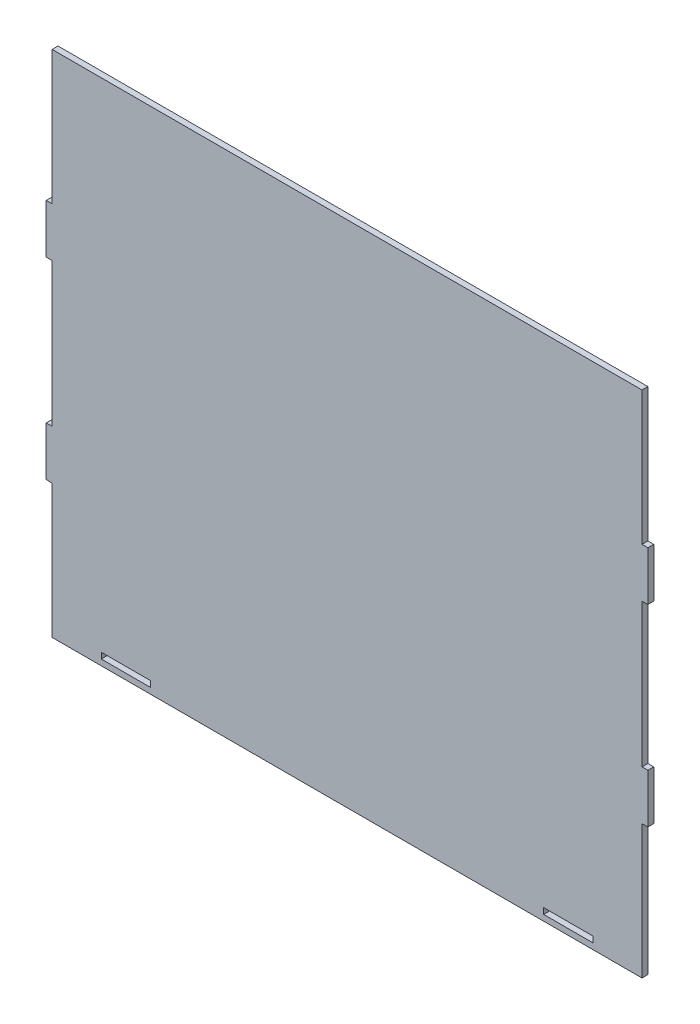
SolidWorks part; units mm, degrees
material "Maple"
ref_plane "Front Plane" through (0, 0, 0) normal (0, 0, 1) x (1, 0, 0)
ref_plane "Top Plane" through (0, 0, 0) normal (0, 1, 0) x (1, 0, 0)
ref_plane "Right Plane" through (0, 0, 0) normal (1, 0, 0) x (0, 0, -1)
sketch "Sketch1" plane through (0, 0, 0) normal (0, 0, 1) x (1, 0, 0)
  line L0 (-450, 0) -> (0, 0) construction
  line L1 (-300, 259) -> (300, 259)
  line L2 (-300, 259) -> (-300, 123)
  line L3 (-300, -259) -> (300, -259)
  line L4 (300, 259) -> (300, 123)
  line L5 (-300, 259) -> (300, -259) construction
  line L6 (-300, -259) -> (300, 259) construction
  line L7 (-306, 123) -> (-300, 123)
  line L8 (-306, 123) -> (-306, 73)
  line L9 (-306, 73) -> (-300, 73)
  line L11 (-300, 207) -> (-282.5, 182) construction
  line L12 (-300, -123) -> (-300, -259)
  line L13 (0, 259) -> (0, -259) construction
  line L14 (306, 73) -> (300, 73)
  line L15 (306, 123) -> (306, 73)
  line L16 (306, 123) -> (300, 123)
  line L17 (306, -73) -> (300, -73)
  line L18 (306, -123) -> (300, -123)
  line L19 (306, -123) -> (306, -73)
  line L20 (-306, -73) -> (-300, -73)
  line L22 (-306, -123) -> (-300, -123)
  line L23 (-306, -123) -> (-306, -73)
  line L24 (-300, 73) -> (-300, -73)
  line L25 (300, -123) -> (300, -259)
  line L26 (300, 73) -> (300, -73)
  line L27 (-225, 0) -> (-225, -259) construction
  line L28 (250, -253) -> (200, -253)
  line L29 (-250, -247) -> (-200, -247)
  line L30 (-250, -247) -> (-250, -253)
  line L31 (-250, -253) -> (-200, -253)
  line L32 (-200, -247) -> (-200, -253)
  line L33 (-250, -247) -> (-200, -253) construction
  line L34 (-250, -253) -> (-200, -247) construction
  line L35 (200, -247) -> (200, -253)
  line L36 (250, -247) -> (200, -247)
  line L37 (250, -247) -> (250, -253)
  point P0 (0, 0)
  point P6 (-300, 207)
  point P31 (-225, -250)
  point P41 (0, 0)
  dimension "D1" = 600
  dimension "D2" = 518
  dimension "D3" = 136
  dimension "D4" = 50
  dimension "D5" = 50
  dimension "D6" = 6
  dimension "D7" = 6
  dimension "D8" = 136
  dimension "D9" = 136
  dimension "D10" = 136
  dimension "D11" = 50
  dimension "D15" = 6
extrude "Boss-Extrude1" add sketch "Sketch1" along normal blind 6
